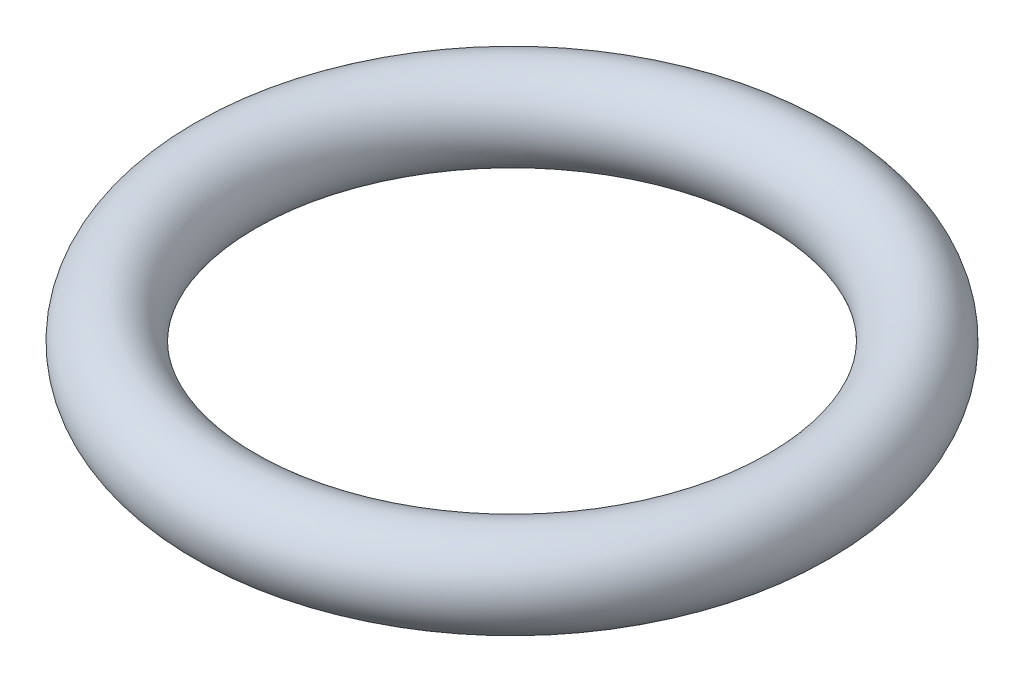
SolidWorks part; units mm, degrees
material "HYPALON"
ref_plane "Alzado" through (0, 0, 0) normal (0, 0, 1) x (1, 0, 0)
ref_plane "Planta" through (0, 0, 0) normal (0, 1, 0) x (1, 0, 0)
ref_plane "Vista lateral" through (0, 0, 0) normal (1, 0, 0) x (0, 0, -1)
sketch "Croquis2" plane through (0, 0, 0) normal (0, 0, 1) x (1, 0, 0)
  line L1 (0, 1) -> (0, -1) construction
  circle A0 centre (5, 0) radius 0.75
  point P7 (0, 0)
  dimension "D2" = 1.5
  dimension "D1" = 5
  dimension "D3" = 2
revolve "Revolución1" add sketch "Croquis2" angle 360 about L1
